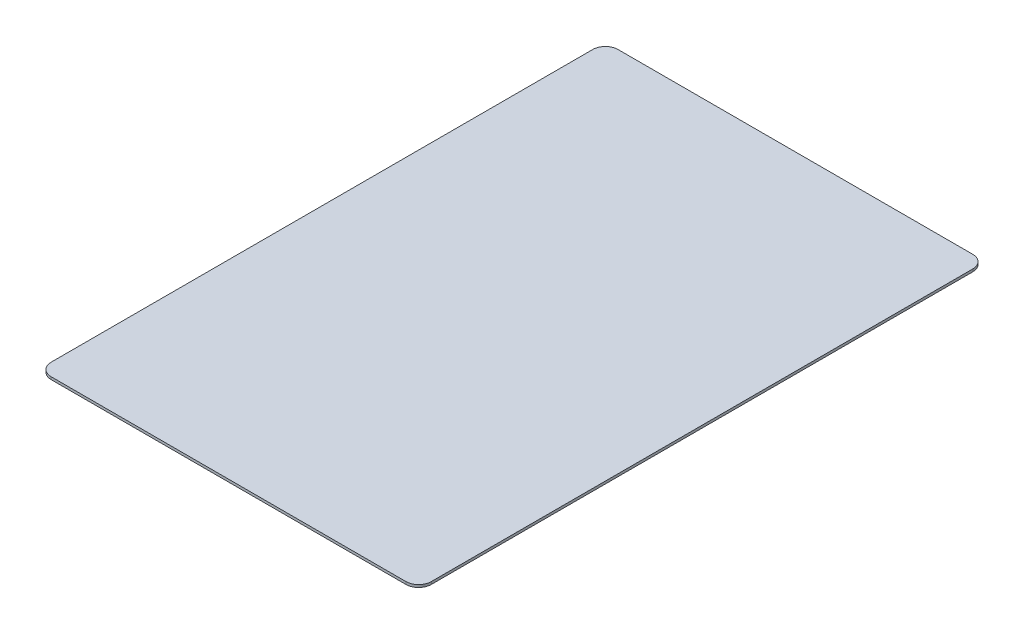
SolidWorks part; units mm, degrees
ref_plane "Front Plane" through (0, 0, 0) normal (0, 0, 1) x (1, 0, 0)
ref_plane "Top Plane" through (0, 0, 0) normal (0, 1, 0) x (1, 0, 0)
ref_plane "Right Plane" through (0, 0, 0) normal (1, 0, 0) x (0, 0, -1)
sketch "Sketch1" plane through (0, -440.405, -903.5614) normal (0, 1, 0) x (0, 0, -1)
  line L9 (-616.5066, -191.405) -> (-616.5066, -491.405)
  line L14 (-616.5066, -491.405) -> (-169.0937, -491.405)
  line L15 (-169.0937, -191.405) -> (-169.0937, -491.405)
  line L16 (-616.5066, -191.405) -> (-169.0937, -191.405)
extrude "Boss-Extrude1" add sketch "Sketch1" along normal blind 2 contours L15 L14 L9 L16
ref_plane "Plane1" through (0, 0, -510.7612) normal (0, 0, 1) x (1, 0, 0)
ref_plane "Plane2" through (341.405, 0, 0) normal (1, 0, 0) x (0, -1, 0)
fillet "Fillet1" radius 10 4 edges at (491.405, -439.405, -287.0548) (491.405, -439.405, -734.4677) (191.405, -439.405, -734.4677) (191.405, -439.405, -287.0548)
